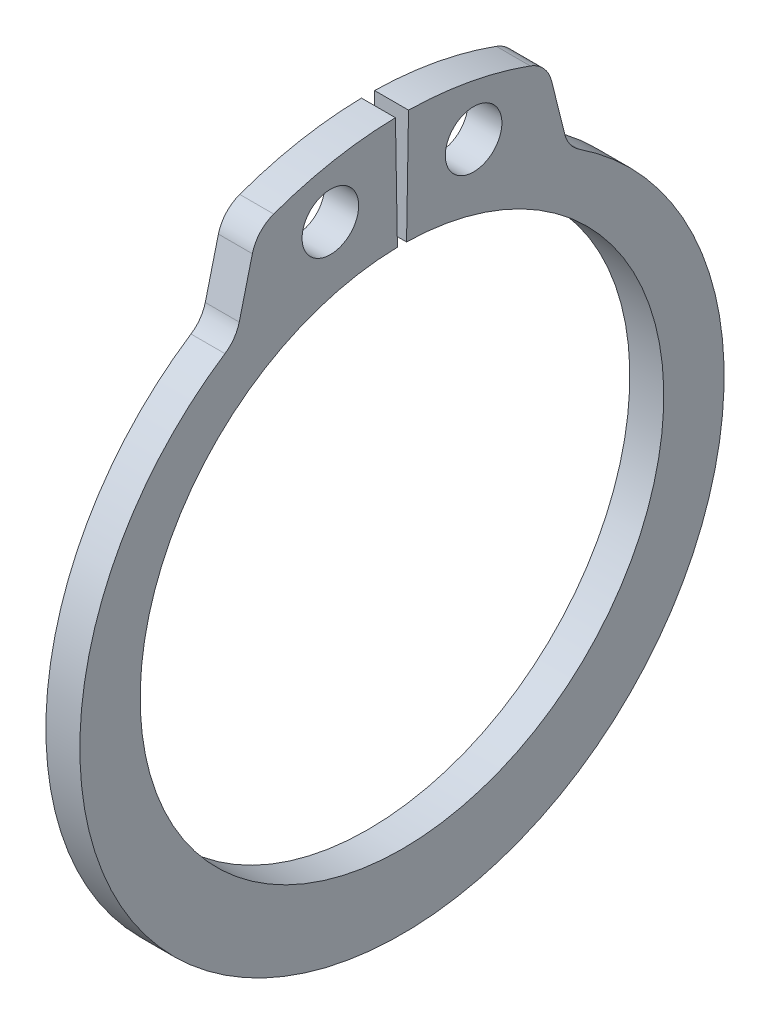
SolidWorks part; units mm, degrees
material "Cast Carbon Steel"
ref_plane "Front" through (0, 0, 0) normal (0, 0, 1) x (1, 0, 0)
ref_plane "Top" through (0, 0, 0) normal (0, 1, 0) x (1, 0, 0)
ref_plane "Right" through (0, 0, 0) normal (1, 0, 0) x (0, 0, -1)
sketch "Sketch1" plane through (0, 0, 0) normal (1, 0, 0) x (0, 0, -1)
  line L0 (0, 0) -> (0, 9.25) construction
  line L1 (-0.1614, 9.2486) -> (-0.2312, 13.248)
  line L2 (-0.2312, 13.248) -> (-4.8989, 13.1665) construction
  line L3 (-4.8989, 13.1665) -> (-5.8665, 9.2853) construction
  line L4 (0.2312, 13.248) -> (0.1614, 9.2486)
  line L5 (0.2312, 13.248) -> (4.8989, 13.1665) construction
  line L6 (4.8989, 13.1665) -> (5.8665, 9.2853) construction
  line L7 (-5.8665, 9.2853) -> (-4.9407, 7.82) construction
  line L8 (5.8665, 9.2853) -> (4.9407, 7.82) construction
  line L9 (0, -9.25) -> (0, -11.85) construction
  line L10 (-4.8989, 13.1665) -> (-0.1614, 9.2486) construction
  line L11 (-9.25, 0) -> (9.25, 0) construction
  line L12 (0, 9.25) -> (0, 13.25) construction
  line L13 (5.1364, 12.2139) -> (5.8665, 9.2853)
  line L14 (-5.1364, 12.2139) -> (-5.8665, 9.2853)
  circle A0 centre (0, 0) radius 9.25 construction
  arc A1 (-0.1614, 9.2486) -> (0.1614, 9.2486) centre (0, 0) ccw
  circle A2 centre (0, -0.4681) radius 11.3819 construction
  circle A4 centre (-2.5301, 11.2075) radius 1
  circle A5 centre (2.5301, 11.2075) radius 1
  arc A6 (-5.8665, 9.2853) -> (5.8665, 9.2853) centre (0, -0.4681) ccw
  arc A7 (0.2312, 13.248) -> (5.1364, 12.2139) centre (0, 0) cw
  arc A8 (-0.2312, 13.248) -> (-5.1364, 12.2139) centre (0, 0) ccw
  dimension "D1" = 75
  dimension "A" = 18.5
  dimension "Hole" = 2
  dimension "Smin" = 1.7333
  dimension "Smax" = 2.6
  dimension "H" = 4
  dimension "Angle" = 1
extrude "Extrude1" add sketch "Sketch1" along normal mid plane 1.2
fillet "Fillet1" radius 1.2 4 edges at (0, 9.2853, 5.8665) (0, 12.2139, 5.1364) (0, 12.2139, -5.1364) (0, 9.2853, -5.8665)
sketch "Sketch2" plane through (0, 0, 0) normal (0, 0, 1) x (1, 0, 0)
  line L0 (-3.25, 0) -> (9.75, 0)
  line L1 (9.75, 0) -> (9.75, -10)
  line L2 (-3.25, 0) -> (-3.25, -9.5)
  line L3 (9.75, -10) -> (0.65, -10)
  line L4 (0.65, -10) -> (0.65, -9.5)
  line L5 (0.65, -9.5) -> (-0.65, -9.5)
  line L6 (-0.65, -9.5) -> (-0.65, -10)
  line L7 (-0.65, -10) -> (-3.25, -10) construction
  line L8 (-3.25, -10) -> (-3.25, 0) construction
  line L9 (0, -9.5) -> (0, 0) construction
  line L10 (9.75, 0) -> (14.0551, 0) construction
  line L11 (-3.25, -9.5) -> (-2.75, -10)
  line L12 (-2.75, -10) -> (-0.65, -10)
  dimension "D1" = 45
  dimension "Dg" = 19
  dimension "Ds" = 20
  dimension "D2" = 13
  dimension "W" = 1.3
  dimension "D3" = 3.25
revolve "Revolve1" [suppressed] add sketch "Sketch2" angle 360 about L10
equation "\"D2@Sketch2\" = \"W@Sketch2\"*10"
equation "\"D3@Sketch2\" = \"D2@Sketch2\"/4"
equation "\"Smin@Sketch1\" = \"Smax@Sketch1\"/1.5"
equation "\"D1@Fillet1\" = \"D1@Extrude1\""
